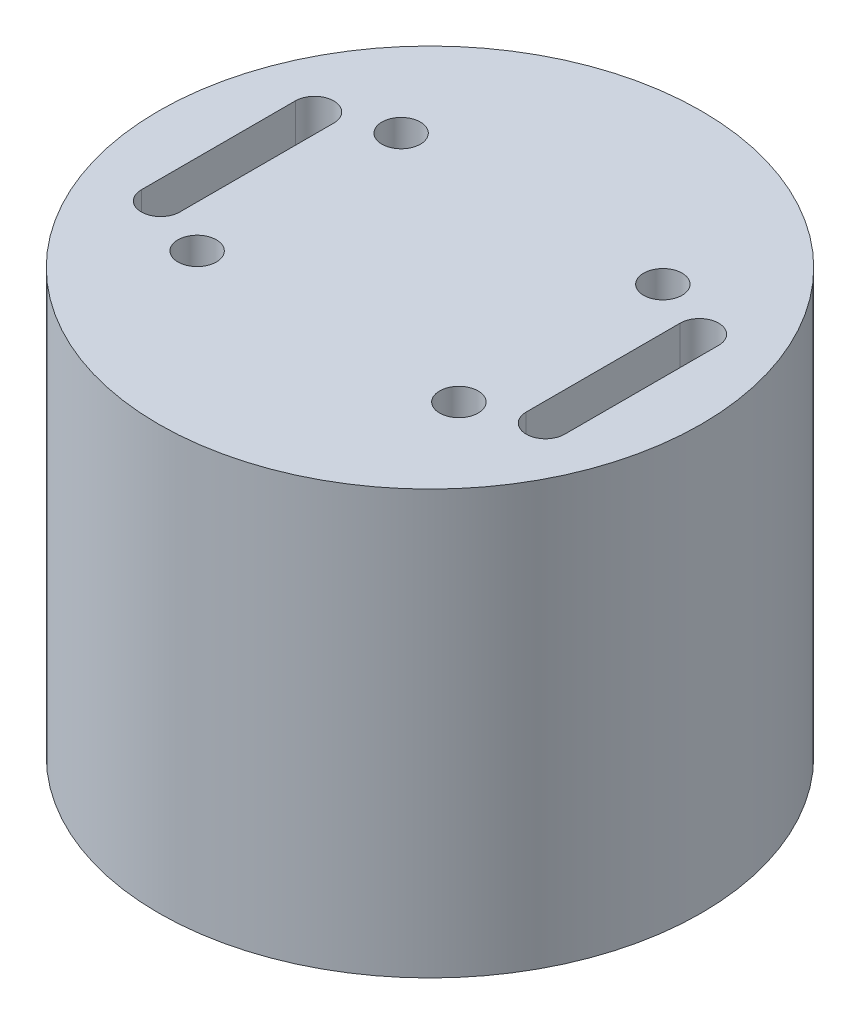
SolidWorks part; units mm, degrees
ref_plane "Front Plane" through (0, 0, 0) normal (0, 0, 1) x (1, 0, 0)
ref_plane "Top Plane" through (0, 0, 0) normal (0, 1, 0) x (1, 0, 0)
ref_plane "Right Plane" through (0, 0, 0) normal (1, 0, 0) x (0, 0, -1)
sketch "Sketch1" plane through (0, 0, 0) normal (0, 1, 0) x (1, 0, 0)
  circle A0 centre (0, 0) radius 70.5
  dimension "D1" = 141
extrude "Boss-Extrude1" add sketch "Sketch1" along normal blind 10
sketch "Sketch2" plane through (0, 10, 0) normal (0, 1, 0) x (1, 0, 0)
  line L1 (-34, 26.5) -> (34, 26.5) construction
  line L2 (-34, 26.5) -> (-34, -26.5) construction
  line L3 (-34, -26.5) -> (34, -26.5) construction
  line L4 (34, 26.5) -> (34, -26.5) construction
  line L5 (-34, 26.5) -> (34, -26.5) construction
  line L6 (-34, -26.5) -> (34, 26.5) construction
  circle A0 centre (-34, -26.5) radius 5
  circle A1 centre (34, -26.5) radius 5
  circle A2 centre (34, 26.5) radius 5
  circle A3 centre (-34, 26.5) radius 5
  point P0 (0, 0)
  dimension "D3" = 10
  dimension "D1" = 68
  dimension "D2" = 53
extrude "Cut-Extrude1" cut sketch "Sketch2" against normal through all
sketch "Sketch3" plane through (0, 0, 0) normal (0, -1, 0) x (1, 0, 0)
  circle A0 centre (0, 0) radius 70.5
  circle A1 centre (0, 0) radius 60.5
  dimension "D1" = 141
  dimension "D2" = 10
extrude "Boss-Extrude2" add sketch "Sketch3" along normal blind 100
sketch "Sketch4" plane through (0, 10, 0) normal (0, 1, 0) x (1, 0, 0)
  line L0 (50, 20) -> (50, -20) construction
  line L1 (55, 20) -> (55, -20)
  line L2 (45, 20) -> (45, -20)
  arc A0 (55, 20) -> (45, 20) centre (50, 20) ccw
  arc A1 (45, -20) -> (55, -20) centre (50, -20) ccw
  point P2 (50, 0)
  point P7 (0, 0)
  dimension "D2" = 5
  dimension "D1" = 50
  dimension "D3" = 20
extrude "Cut-Extrude2" cut sketch "Sketch4" against normal through all
mirror "Mirror1" about plane through (0, 0, 0) normal (1, 0, 0) of "Cut-Extrude2"
